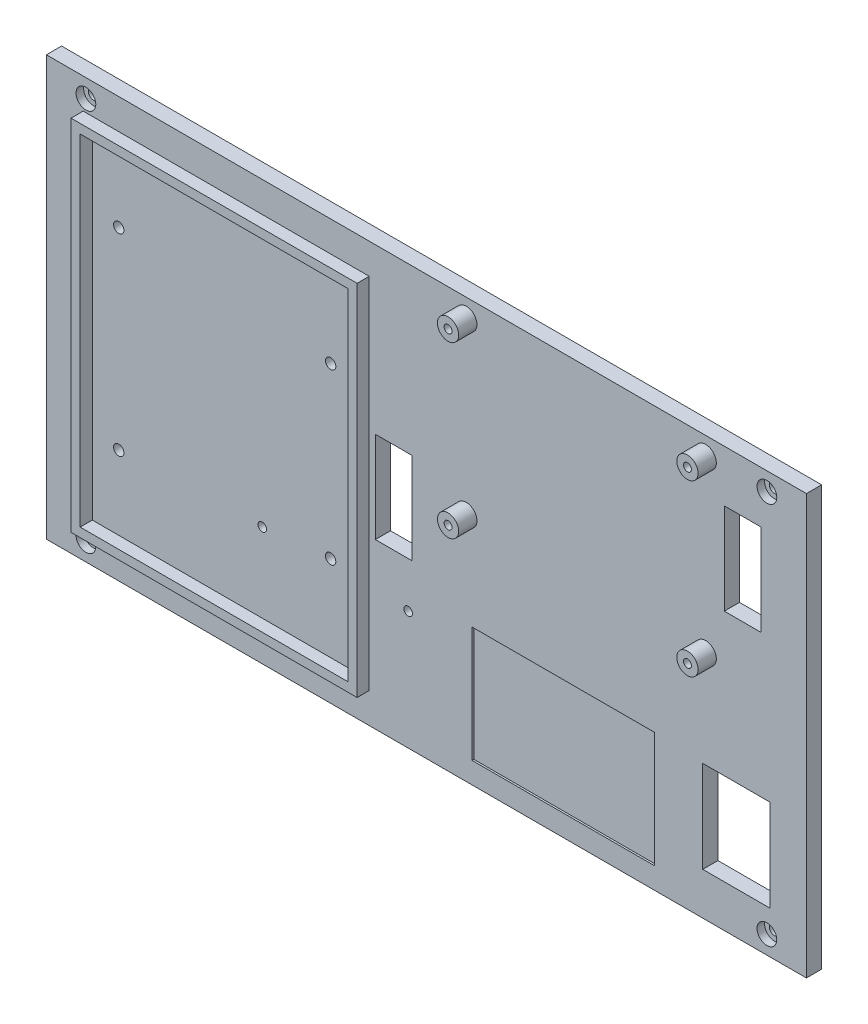
SolidWorks part; units mm, degrees
ref_plane "Front Plane" through (0, 0, 0) normal (0, 0, 1) x (1, 0, 0)
ref_plane "Top Plane" through (0, 0, 0) normal (0, 1, 0) x (1, 0, 0)
ref_plane "Right Plane" through (0, 0, 0) normal (1, 0, 0) x (0, 0, -1)
ref_plane "P_Front_98" through (0, 0, 98) normal (0, 0, 1) x (1, 0, 0)
sketch "Sketch1" plane through (0, 0, 98) normal (0, 0, 1) x (1, 0, 0)
  line L0 (-125, -69) -> (125, -69)
  line L1 (125, -69) -> (125, 69)
  line L2 (125, 69) -> (-125, 69)
  line L3 (-125, 69) -> (-125, -69)
extrude "Plate" add sketch "Sketch1" along normal blind 5
ref_plane "P_Front_103" through (0, 0, 103) normal (0, 0, 1) x (1, 0, 0)
sketch "Sketch2" plane through (0, 0, 103) normal (0, 0, 1) x (1, 0, 0)
  line L0 (-112.9, -59) -> (-18.8, -59)
  line L1 (-18.8, -59) -> (-18.8, 59)
  line L2 (-18.8, 59) -> (-112.9, 59)
  line L3 (-112.9, 59) -> (-112.9, -59)
  line L4 (-109.9, -56) -> (-21.8, -56)
  line L5 (-21.8, -56) -> (-21.8, 56)
  line L6 (-21.8, 56) -> (-109.9, 56)
  line L7 (-109.9, 56) -> (-109.9, -56)
extrude "Arm_locating_fence" add sketch "Sketch2" along normal blind 4
ref_plane "P_Front_97" through (0, 0, 97) normal (0, 0, 1) x (1, 0, 0)
sketch "Sketch3" plane through (0, 0, 97) normal (0, 0, 1) x (1, 0, 0)
  circle A0 centre (-101.2, 31.7) radius 1.7
  circle A1 centre (-101.2, -31.7) radius 1.7
  circle A2 centre (-31.5, 27.8) radius 1.7
  circle A3 centre (-31.5, -27.8) radius 1.7
extrude "Arm_M3_holes" cut sketch "Sketch3" along normal blind 7
sketch "Sketch4" plane through (0, 0, 97) normal (0, 0, 1) x (1, 0, 0)
  circle A0 centre (-112, 63) radius 1.7
  circle A1 centre (-112, -63) radius 1.7
  circle A2 centre (112, 63) radius 1.7
  circle A3 centre (112, -63) radius 1.7
extrude "Deck_M3_holes" cut sketch "Sketch4" along normal blind 7
sketch "Sketch5" plane through (0, 0, 103) normal (0, 0, 1) x (1, 0, 0)
  circle A0 centre (-112, 63) radius 3.25
  circle A1 centre (-112, -63) radius 3.25
  circle A2 centre (112, 63) radius 3.25
  circle A3 centre (112, -63) radius 3.25
extrude "Deck_counterbores" cut sketch "Sketch5" against normal blind 2.5
sketch "Sketch6" plane through (0, 0, 97) normal (0, 0, 1) x (1, 0, 0)
  line L0 (90.9, -55.1) -> (113.1, -55.1)
  line L1 (113.1, -55.1) -> (113.1, -24.9)
  line L2 (113.1, -24.9) -> (90.9, -24.9)
  line L3 (90.9, -24.9) -> (90.9, -55.1)
extrude "Kill_switch_cutout" cut sketch "Sketch6" along normal blind 7
sketch "Sketch7" plane through (0, 0, 97) normal (0, 0, 1) x (1, 0, 0)
  line L0 (-16.8, -15) -> (-4.8, -15)
  line L1 (-4.8, -15) -> (-4.8, 15)
  line L2 (-4.8, 15) -> (-16.8, 15)
  line L3 (-16.8, 15) -> (-16.8, -15)
extrude "Servo_cable_slot" cut sketch "Sketch7" along normal blind 7
sketch "Sketch8" plane through (0, 0, 97) normal (0, 0, 1) x (1, 0, 0)
  circle A0 centre (-6, -30) radius 1.4
  circle A1 centre (-54, -30) radius 1.4
extrude "ESP32_standoff_holes_M2p5" cut sketch "Sketch8" along normal blind 7
sketch "Sketch9" plane through (0, 0, 103) normal (0, 0, 1) x (1, 0, 0)
  circle A0 centre (13.13, 7.06) radius 3.5
  circle A1 centre (13.13, 62.94) radius 3.5
  circle A2 centre (91.87, 7.06) radius 3.5
  circle A3 centre (91.87, 62.94) radius 3.5
extrude "MDD10A_bosses" add sketch "Sketch9" along normal blind 6
sketch "Sketch10" plane through (0, 0, 97) normal (0, 0, 1) x (1, 0, 0)
  circle A0 centre (13.13, 7.06) radius 1.3
  circle A1 centre (13.13, 62.94) radius 1.3
  circle A2 centre (91.87, 7.06) radius 1.3
  circle A3 centre (91.87, 62.94) radius 1.3
extrude "MDD10A_pilots_M3" cut sketch "Sketch10" along normal blind 13
sketch "Sketch11" plane through (0, 0, 97) normal (0, 0, 1) x (1, 0, 0)
  line L0 (98, 22) -> (110, 22)
  line L1 (110, 22) -> (110, 52)
  line L2 (110, 52) -> (98, 52)
  line L3 (98, 52) -> (98, 22)
extrude "Motor_wire_slot" cut sketch "Sketch11" along normal blind 7
ref_plane "P_Front_102p4" through (0, 0, 102.4) normal (0, 0, 1) x (1, 0, 0)
sketch "Sketch12" plane through (0, 0, 102.4) normal (0, 0, 1) x (1, 0, 0)
  line L0 (15, -62) -> (75, -62)
  line L1 (75, -62) -> (75, -24)
  line L2 (75, -24) -> (15, -24)
  line L3 (15, -24) -> (15, -62)
extrude "Name_plate_recess" cut sketch "Sketch12" along normal blind 1.6
